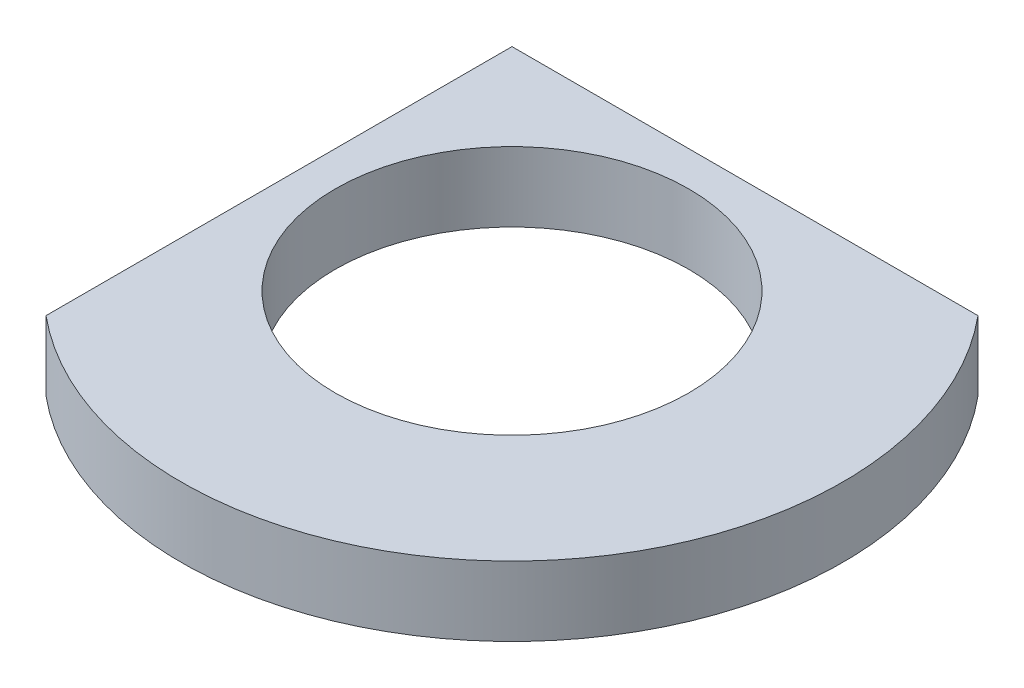
SolidWorks part; units mm, degrees
ref_plane "前视基准面" through (0, 0, 0) normal (0, 0, 1) x (1, 0, 0)
ref_plane "上视基准面" through (0, 0, 0) normal (0, 1, 0) x (1, 0, 0)
ref_plane "右视基准面" through (0, 0, 0) normal (1, 0, 0) x (0, 0, -1)
sketch "草图1" plane through (0, 0, 0) normal (0, 1, 0) x (1, 0, 0)
  circle A0 centre (0, 0) radius 10.15
  circle A1 centre (0, 0) radius 19
  dimension "D1" = 20.3
  dimension "D2" = 38
extrude "凸台-拉伸2" add sketch "草图1" along normal blind 4
sketch "草图3" plane through (0, 4, 0) normal (0, 1, 0) x (1, 0, 0)
  line L1 (-19, 22.15) -> (19, 22.15)
  line L2 (-19, 22.15) -> (-19, 12.15)
  line L3 (-19, 12.15) -> (19, 12.15)
  line L4 (19, 22.15) -> (19, 12.15)
  circle A0 centre (0, 0) radius 19 construction
  dimension "D1" = 12.15
  dimension "D2" = 10
extrude "切除-拉伸8" cut sketch "草图3" against normal through all
sketch "草图4" plane through (0, 4, 0) normal (0, 1, 0) x (1, 0, 0)
  line L0 (-14.6074, 12.15) -> (14.6074, 12.15) construction
  line L1 (-22.15, 12.15) -> (-12.15, 12.15)
  line L2 (-22.15, 12.15) -> (-22.15, -19)
  line L3 (-22.15, -19) -> (-12.15, -19)
  line L4 (-12.15, 12.15) -> (-12.15, -19)
  arc A0 (-14.6074, 12.15) -> (14.6074, 12.15) centre (0, 0) ccw construction
  dimension "D1" = 12.15
  dimension "D2" = 10
extrude "切除-拉伸9" cut sketch "草图4" against normal through all
